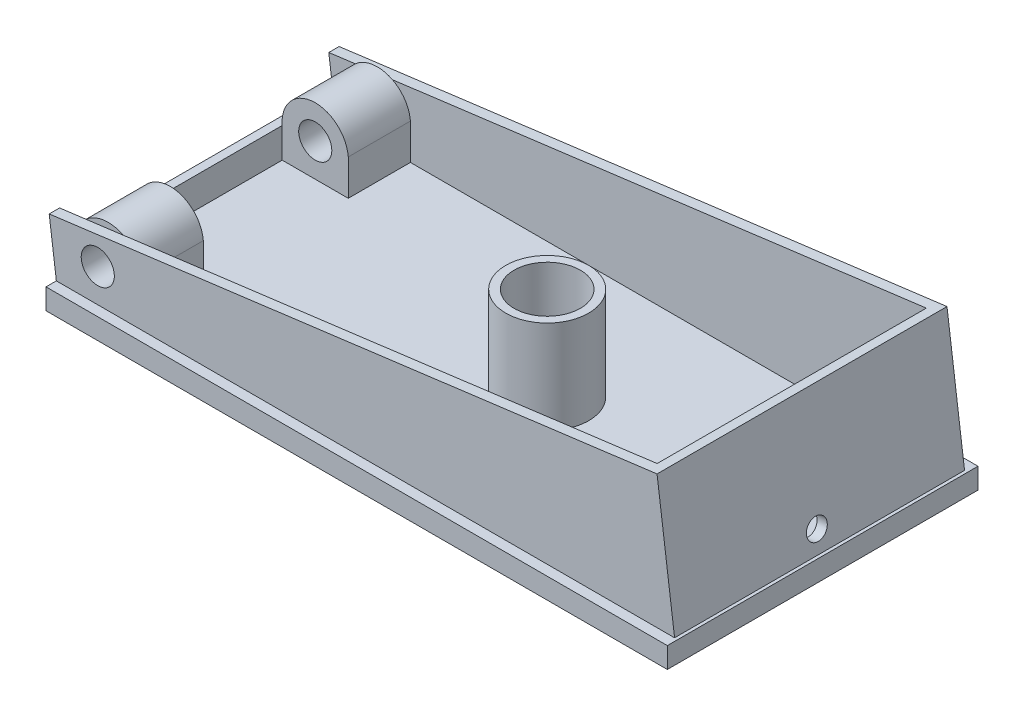
SolidWorks part; units mm, degrees
ref_plane "Front Plane" through (0, 0, 0) normal (0, 0, 1) x (1, 0, 0)
ref_plane "Top Plane" through (0, 0, 0) normal (0, 1, 0) x (1, 0, 0)
ref_plane "Right Plane" through (0, 0, 0) normal (1, 0, 0) x (0, 0, -1)
sketch "Sketch1" plane through (0, 0, 0) normal (0, 1, 0) x (1, 0, 0)
  line L1 (75, -37.5) -> (-75, -37.5)
  line L2 (75, -37.5) -> (75, 37.5)
  line L3 (75, 37.5) -> (-75, 37.5)
  line L4 (-75, -37.5) -> (-75, 37.5)
  line L5 (75, -37.5) -> (-75, 37.5) construction
  line L6 (75, 37.5) -> (-75, -37.5) construction
  point P0 (0, 0)
  dimension "D1" = 75
  dimension "D2" = 150
extrude "Boss-Extrude1" add sketch "Sketch1" along normal mid plane 5
sketch "Sketch7" plane through (0, 0, 0) normal (0, 0, 1) x (1, 0, 0)
  line L0 (-75, 2.5) -> (70.0174, 34.6496) construction
  line L1 (70.0174, 34.6496) -> (74.25, 2.5)
  line L2 (74.25, 2.5) -> (-75, 2.5)
  line L3 (-75, 2.5) -> (-76.7315, 15.6354)
  line L4 (-75, 2.5) -> (75, 2.5) construction
  line L5 (75, 2.5) -> (75, -2.5) construction
  line L6 (-76.7315, 15.6354) -> (70.0174, 34.6496)
  dimension "D1" = 12.5
  dimension "D2" = 82.5
  dimension "D3" = 0.75
extrude "Boss-Extrude5" add sketch "Sketch7" along normal blind 2.5 from offset 32.5 contours L1 L2 L3 L6
sketch "Sketch2" plane through (0, 2.5, 0) normal (0, 1, 0) x (1, 0, 0)
  line L0 (0, 44.9914) -> (0, -49.4023) construction
  line L1 (-73.7254, 0) -> (79.9007, 0) construction
  circle A0 centre (8.5, 0) radius 10
  circle A1 centre (8.5, 0) radius 8
  dimension "D1" = 20
  dimension "D2" = 16
  dimension "D3" = 8.5
sketch "Sketch3" plane through (0, 0, 0) normal (0, 0, 1) x (1, 0, 0)
  line L0 (-72.9735, 2.5) -> (-72.9735, 11.1511)
  line L1 (-73.7254, 2.5) -> (79.9007, 2.5) construction
  line L2 (-57.0265, 11.1511) -> (-57.0265, 2.5)
  line L3 (-72.9735, 2.5) -> (-57.0265, 2.5)
  line L4 (-65, 21.5815) -> (-65, -6.7629) construction
  arc A0 (-72.9735, 11.1511) -> (-57.0265, 11.1511) centre (-65, 10.5) cw
  circle A1 centre (-65, 10.5) radius 4
  dimension "D1" = 8
  dimension "D3" = 8
  dimension "D2" = 8
  dimension "D4" = 65
extrude "Boss-Extrude2" add sketch "Sketch3" along normal up to surface (15 mm away) from offset 17.5 up to face at (-1.866, 13.8212, 32.5)
mirror "Mirror1" about plane through (0, 0, 0) normal (0, 0, 1) of "Boss-Extrude5", "Boss-Extrude2"
extrude "Boss-Extrude3" add sketch "Sketch2" along normal blind 22.5
sketch "Sketch5" plane through (0, 2.5, 0) normal (0, 1, 0) x (1, 0, 0)
  line L0 (-72.9735, -32.5) -> (-75, -32.5)
  line L1 (-75, 37.5) -> (-75, 35) construction
  line L2 (-75, -32.5) -> (-75, 32.5)
  line L3 (-75, 32.5) -> (-72.9735, 32.5)
  line L4 (-72.9735, 32.5) -> (-72.9735, -32.5)
  line L6 (-75, 32.5) -> (-75, -32.5) construction
  line L7 (74.25, -32.5) -> (-57.0265, -32.5) construction
  line L8 (-76.7315, -32.5) -> (-70.3313, -32.5) construction
  line L9 (-72.9735, -32.5) -> (-72.9735, -17.5) construction
  line L10 (-76.7315, 32.5) -> (-70.3313, 32.5) construction
extrude "Boss-Extrude4" add sketch "Sketch5" along normal blind 7.25
sketch "Sketch8" plane through (0, 0, -32.5) normal (0, 0, 1) x (1, 0, 0)
  line L0 (70.0174, 34.6496) -> (74.25, 2.5)
  line L1 (74.25, 2.5) -> (71.7284, 2.5)
  line L2 (74.25, 2.5) -> (-75, 2.5) construction
  line L3 (71.7284, 2.5) -> (67.5381, 34.3284)
  line L5 (67.5381, 34.3284) -> (70.0174, 34.6496)
  line L6 (-76.7315, 15.6354) -> (70.0174, 34.6496) construction
  dimension "D1" = 2.5
extrude "Boss-Extrude6" add sketch "Sketch8" along normal up to surface (65 mm away) up to face at (-6.0617, 13.7982, 32.5)
sketch "Sketch9" plane through (0, 0, 35) normal (0, 0, 1) x (1, 0, 0)
  circle A0 centre (-65, 10.5) radius 4
extrude "Cut-Extrude1" cut sketch "Sketch9" against normal through all both and the other way through all
sketch "Sketch13" plane through (73.3085, 9.6512, 0) normal (0.9914, 0.1305, 0) x (0, 0, -1)
  line L2 (-35, -7.213) -> (35, -7.213) construction
  circle A0 centre (0, -2.213) radius 2.5
  dimension "D1" = 5
  dimension "D2" = 5
extrude "Cut-Extrude4" cut sketch "Sketch13" against normal blind 5
